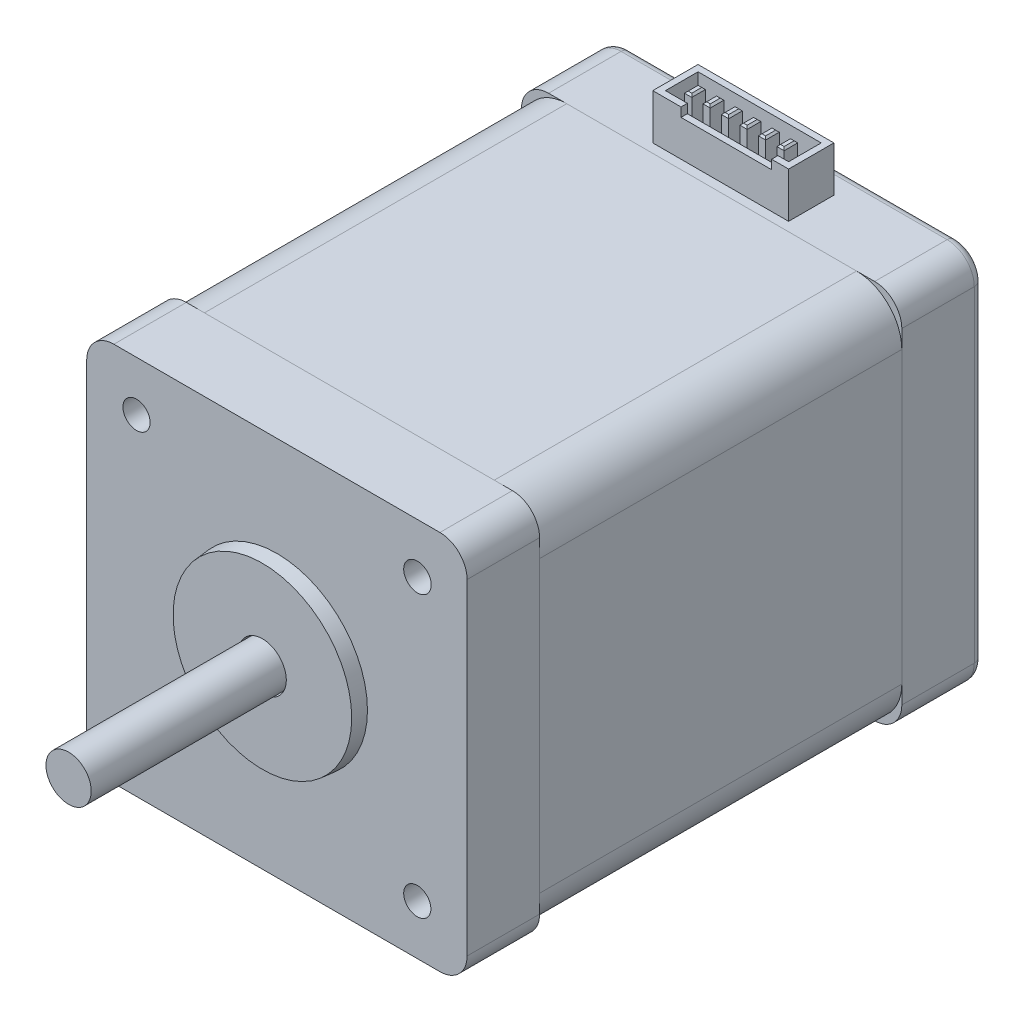
SolidWorks part; units mm, degrees
material "氧化铝"
ref_plane "前视基准面" through (0, 0, 0) normal (0, 0, 1) x (1, 0, 0)
ref_plane "上视基准面" through (0, 0, 0) normal (0, 1, 0) x (1, 0, 0)
ref_plane "右视基准面" through (0, 0, 0) normal (1, 0, 0) x (0, 0, -1)
sketch "草图1" plane through (0, 0, 0) normal (0, 0, 1) x (1, 0, 0)
  line L0 (0, 21) -> (0, -21) construction
  line L1 (-18, 21) -> (18, 21)
  line L2 (-21, 18) -> (-21, -18)
  line L3 (-18, -21) -> (18, -21)
  line L4 (21, 18) -> (21, -18)
  line L5 (-21, 21) -> (21, -21) construction
  line L6 (-21, -21) -> (21, 21) construction
  line L7 (-15.5, 15.5) -> (15.5, 15.5) construction
  line L8 (-15.5, 15.5) -> (-15.5, -15.5) construction
  line L9 (-15.5, -15.5) -> (15.5, -15.5) construction
  line L10 (15.5, 15.5) -> (15.5, -15.5) construction
  line L11 (-15.5, 15.5) -> (15.5, -15.5) construction
  line L12 (-15.5, -15.5) -> (15.5, 15.5) construction
  line L13 (-21, 0) -> (21, 0) construction
  circle A0 centre (-15.5, 15.5) radius 1.5
  circle A1 centre (15.5, 15.5) radius 1.5
  circle A2 centre (15.5, -15.5) radius 1.5
  circle A3 centre (-15.5, -15.5) radius 1.5
  arc A4 (-18, -21) -> (-21, -18) centre (-18, -18) cw
  arc A5 (18, -21) -> (21, -18) centre (18, -18) ccw
  arc A6 (21, 18) -> (18, 21) centre (18, 18) ccw
  arc A7 (-21, 18) -> (-18, 21) centre (-18, 18) cw
  point P0 (0, 0)
  point P6 (0, 0)
  dimension "D4" = 3
  dimension "D5" = 3
  dimension "D1" = 42
  dimension "D2" = 42
  dimension "D3" = 31
extrude "凸台-拉伸1" add sketch "草图1" along normal blind 8
sketch "草图4" plane through (0, 0, 8) normal (0, 0, 1) x (1, 0, 0)
  circle A0 centre (0, 0) radius 2.5
  dimension "D1" = 5
extrude "凸台-拉伸2" add sketch "草图4" along normal blind 23
sketch "草图9" plane through (0, 0, 0) normal (0, 0, -1) x (-1, 0, 0)
  line L1 (-21, 21) -> (21, 21)
  line L2 (-21, 21) -> (-21, -21)
  line L3 (-21, -21) -> (21, -21)
  line L4 (21, 21) -> (21, -21)
  line L5 (-21, 21) -> (21, -21) construction
  line L6 (-21, -21) -> (21, 21) construction
  point P0 (0, 0)
  dimension "D1" = 42
  dimension "D2" = 42
extrude "凸台-拉伸7" add sketch "草图9" along normal blind 40 separate body
sketch "草图10" plane through (0, 0, -40) normal (0, 0, -1) x (-1, 0, 0)
  line L1 (-21, 21) -> (21, 21)
  line L2 (-21, 21) -> (-21, -21)
  line L3 (-21, -21) -> (21, -21)
  line L4 (21, 21) -> (21, -21)
extrude "凸台-拉伸8" add sketch "草图10" along normal blind 9 separate body
fillet "圆角1" radius 3 4 edges at (21, -21, -44.5) (-21, -21, -44.5) (-21, 21, -44.5) (21, 21, -44.5)
fillet "圆角2" radius 5 4 edges at (-21, -21, -20) (-21, 21, -20) (21, 21, -20) (21, -21, -20)
sketch "草图12" plane through (0, 0, 8) normal (0, 0, 1) x (1, 0, 0)
  circle A0 centre (-15.5, 15.5) radius 1.5
  circle A1 centre (15.5185, 15.5) radius 1.5185
  circle A2 centre (-15.5, -15.5) radius 1.5
  circle A3 centre (15.5, -15.5) radius 1.5
extrude "切除-拉伸1" cut sketch "草图12" against normal through all
sketch "草图13" plane through (0, 0, -49) normal (0, 0, -1) x (-1, 0, 0)
  circle A0 centre (0, 0) radius 2.5
extrude "凸台-拉伸9" [suppressed] add sketch "草图13" along normal blind 12
sketch "草图14" plane through (0, 21, 0) normal (0, 1, 0) x (1, 0, 0)
  line L0 (-18, 49) -> (18, 49) construction
  line L1 (-7.5, 46) -> (7.5, 46)
  line L2 (-7.5, 46) -> (-7.5, 41)
  line L3 (-7.5, 41) -> (7.5, 41)
  line L4 (7.5, 46) -> (7.5, 41)
  line L5 (-6.8, 45.3) -> (6.8, 45.3)
  line L6 (6.8, 45.3) -> (6.8, 41.7)
  line L7 (-6.8, 41.7) -> (6.8, 41.7)
  line L8 (-6.8, 45.3) -> (-6.8, 41.7)
  line L9 (-3.66, 44.2073) -> (-2.86, 44.2073)
  line L10 (-5.7, 44.2073) -> (-4.9, 44.2073)
  line L11 (-5.7, 44.2073) -> (-5.7, 42.7073)
  line L12 (-5.7, 42.7073) -> (-4.9, 42.7073)
  line L13 (-4.9, 44.2073) -> (-4.9, 42.7073)
  line L14 (-5.7, 44.2073) -> (-4.9, 42.7073) construction
  line L15 (-5.7, 42.7073) -> (-4.9, 44.2073) construction
  line L16 (-3.66, 44.2073) -> (-3.66, 42.7073)
  line L17 (-3.66, 42.7073) -> (-2.86, 42.7073)
  line L18 (-2.86, 44.2073) -> (-2.86, 42.7073)
  line L19 (-3.66, 44.2073) -> (-2.86, 42.7073) construction
  line L20 (-3.66, 42.7073) -> (-2.86, 44.2073) construction
  line L21 (-1.62, 44.2073) -> (-0.82, 44.2073)
  line L22 (-1.62, 44.2073) -> (-1.62, 42.7073)
  line L23 (-1.62, 42.7073) -> (-0.82, 42.7073)
  line L24 (-0.82, 44.2073) -> (-0.82, 42.7073)
  line L25 (-1.62, 44.2073) -> (-0.82, 42.7073) construction
  line L26 (-1.62, 42.7073) -> (-0.82, 44.2073) construction
  line L27 (0.42, 44.2073) -> (1.22, 44.2073)
  line L28 (0.42, 44.2073) -> (0.42, 42.7073)
  line L29 (0.42, 42.7073) -> (1.22, 42.7073)
  line L30 (1.22, 44.2073) -> (1.22, 42.7073)
  line L31 (0.42, 44.2073) -> (1.22, 42.7073) construction
  line L32 (0.42, 42.7073) -> (1.22, 44.2073) construction
  line L33 (2.46, 44.2073) -> (3.26, 44.2073)
  line L34 (2.46, 44.2073) -> (2.46, 42.7073)
  line L35 (2.46, 42.7073) -> (3.26, 42.7073)
  line L36 (3.26, 44.2073) -> (3.26, 42.7073)
  line L37 (2.46, 44.2073) -> (3.26, 42.7073) construction
  line L38 (2.46, 42.7073) -> (3.26, 44.2073) construction
  line L39 (4.5, 44.2073) -> (5.3, 44.2073)
  line L40 (4.5, 44.2073) -> (4.5, 42.7073)
  line L41 (4.5, 42.7073) -> (5.3, 42.7073)
  line L42 (5.3, 44.2073) -> (5.3, 42.7073)
  line L43 (4.5, 44.2073) -> (5.3, 42.7073) construction
  line L44 (4.5, 42.7073) -> (5.3, 44.2073) construction
  line L45 (0, 49) -> (0, 46) construction
  point P11 (-5.3, 43.4573)
  point P18 (-3.26, 43.4573)
  point P23 (-1.22, 43.4573)
  point P28 (0.82, 43.4573)
  point P33 (2.86, 43.4573)
  point P38 (4.9, 43.4573)
  dimension "D1" = 15
  dimension "D2" = 5
  dimension "D3" = 3
  dimension "D4" = 0.7
  dimension "D5" = 1.5
  dimension "D6" = 0.8
  dimension "D8" = 1.5
  dimension "D9" = 1.5
  dimension "D7" = 6
extrude "凸台-拉伸10" add sketch "草图14" along normal blind 5 contours L4 L1 L2 L3 L8 L5 L6 L7 | L13 L10 L11 L12 | L24 L21 L22 L23 | L42 L39 L40 L41 | L36 L33 L34 L35 | L9 L18 L17 L16 | L27 L30 L29 L28
chamfer "倒角1" distance 0.2 angle 45 24 edges at (4.9, 26, -42.7073) (4.5, 26, -43.4573) (4.9, 26, -44.2073) (5.3, 26, -43.4573) (2.86, 26, -42.7073) (2.46, 26, -43.4573) (2.86, 26, -44.2073) (3.26, 26, -43.4573) (0.82, 26, -44.2073) (1.22, 26, -43.4573) (0.82, 26, -42.7073) (0.42, 26, -43.4573) (-1.22, 26, -42.7073) (-1.62, 26, -43.4573) (-1.22, 26, -44.2073) (-0.82, 26, -43.4573) (-3.26, 26, -44.2073) (-2.86, 26, -43.4573) (-3.26, 26, -42.7073) (-3.66, 26, -43.4573) (-5.3, 26, -42.7073) (-5.7, 26, -43.4573) (-5.3, 26, -44.2073) (-4.9, 26, -43.4573)
sketch "草图15" plane through (0, 0, -41) normal (0, 0, 1) x (1, 0, 0)
  line L0 (0.62, 26) -> (0.62, 22.2151) construction
  line L1 (-4.38, 26) -> (-4.38, 25)
  line L2 (-7.5, 26) -> (7.5, 26) construction
  line L3 (-4.38, 25) -> (5.62, 25)
  line L4 (5.62, 26) -> (5.62, 25)
  line L5 (-4.38, 26) -> (5.62, 26)
  point P9 (0.62, 25)
  dimension "D1" = 5
  dimension "D2" = 1
extrude "切除-拉伸2" cut sketch "草图15" against normal up to next (0.7 mm away)
fillet "圆角3" radius 1 8 edges at (20.1213, 20.1213, -49) (-20.1213, 20.1213, -49) (-21, 0, -49) (-20.1213, -20.1213, -49) (0, -21, -49) (20.1213, -20.1213, -49) (21, 0, -49) (0, 21, -49)
sketch "草图16" plane through (0, 0, 8) normal (0, 0, 1) x (1, 0, 0)
  circle A0 centre (0, 0) radius 10
  circle A1 centre (0, 0) radius 2.5 construction
  circle A2 centre (0, 0) radius 2.5
  dimension "D1" = 20
extrude "凸台-拉伸11" add sketch "草图16" along normal blind 1.6 draft 5
sketch "草图17" plane through (0, 0, -49) normal (0, 0, -1) x (-1, 0, 0)
  circle A0 centre (0, 0) radius 2.5
  dimension "D1" = 5
extrude "凸台-拉伸12" [suppressed] add sketch "草图17" along normal blind 15
ref_plane "基准面2" through (0, 2.5, 0) normal (0, 1, 0) x (1, 0, 0)
sketch "草图18" plane through (0, 2.5, 0) normal (0, 1, 0) x (1, 0, 0)
  line L0 (0, -9.6268) -> (0, -39.7014) construction
  line L1 (1.5, -25.2093) -> (1.5, -17.2093)
  line L2 (-1.5, -25.2093) -> (-1.5, -17.2093)
  line L3 (-2.5, -31) -> (2.5, -31) construction
  line L4 (-1.5, -21.2093) -> (3.1245, -21.2093) construction
  arc A0 (-1.5, -25.2093) -> (1.5, -25.2093) centre (0, -25) ccw
  arc A1 (-1.5, -17.2093) -> (1.5, -17.2093) centre (0, -17.4185) cw
  dimension "D1" = 3
  dimension "D2" = 6
